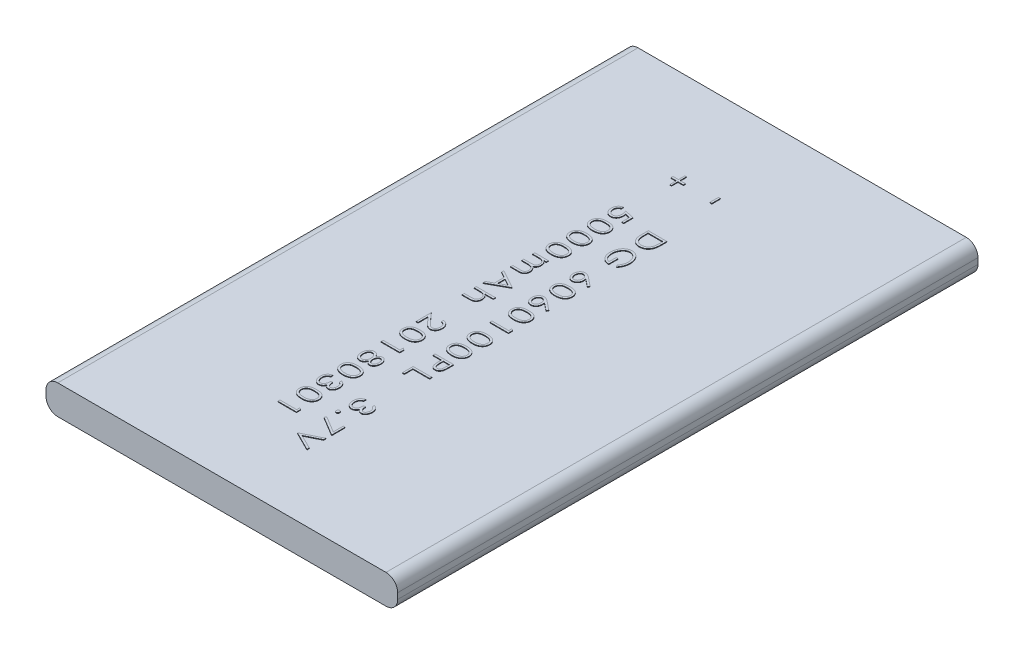
SolidWorks part; units mm, degrees
ref_plane "Front Plane" through (0, 0, 0) normal (0, 0, 1) x (1, 0, 0)
ref_plane "Top Plane" through (0, 0, 0) normal (0, 1, 0) x (1, 0, 0)
ref_plane "Right Plane" through (0, 0, 0) normal (1, 0, 0) x (0, 0, -1)
sketch "Sketch1" plane through (0, 0, 0) normal (0, 1, 0) x (1, 0, 0)
  line L1 (-25.5011, 30.506) -> (34.4989, 30.506)
  line L2 (-25.5011, 30.506) -> (-25.5011, -68.494)
  line L3 (-25.5011, -68.494) -> (34.4989, -68.494)
  line L4 (34.4989, 30.506) -> (34.4989, -68.494)
  dimension "D1" = 60
  dimension "D2" = 99
extrude "Boss-Extrude1" add sketch "Sketch1" along normal blind 5 contours L1 L4 L3 L2
fillet "Fillet1" radius 2 4 edges at (34.4989, 0, 18.994) (34.4989, 5, 18.994) (-25.5011, 0, 18.994) (-25.5011, 5, 18.994)
sketch "Sketch7" plane through (0, 5, 0) normal (0, 1, 0) x (1, 0, 0)
  line L0 (4.4989, 30.506) -> (4.4989, -68.494) construction
  line L1 (-23.5011, 30.506) -> (32.4989, 30.506) construction
  line L2 (-23.5011, -68.494) -> (32.4989, -68.494) construction
  text T0 "  -    DG 6060100PL   3.7V\r\n+   5000mAh  20180301" font "Century Gothic" height 3.175
extrude "Boss-Extrude2" add sketch "Sketch7" along normal blind 0.1
